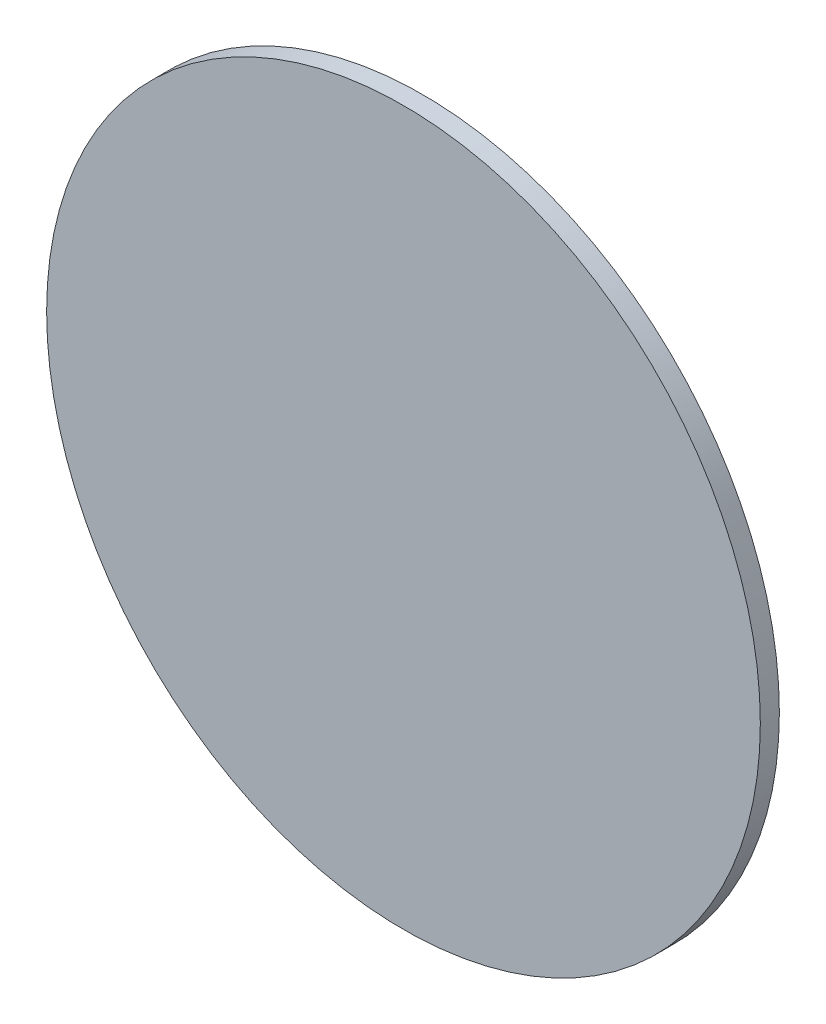
SolidWorks part; units mm, degrees
ref_plane "Alzado" through (0, 0, 0) normal (0, 0, 1) x (1, 0, 0)
ref_plane "Planta" through (0, 0, 0) normal (0, 1, 0) x (1, 0, 0)
ref_plane "Vista lateral" through (0, 0, 0) normal (1, 0, 0) x (0, 0, -1)
sketch "Croquis1" plane through (0, 0, 0) normal (0, 0, 1) x (1, 0, 0)
  circle A0 centre (-34.8288, 5.4993) radius 22.5
  dimension "D1" = 45
extrude "Saliente-Extruir1" add sketch "Croquis1" along normal blind 1.2
